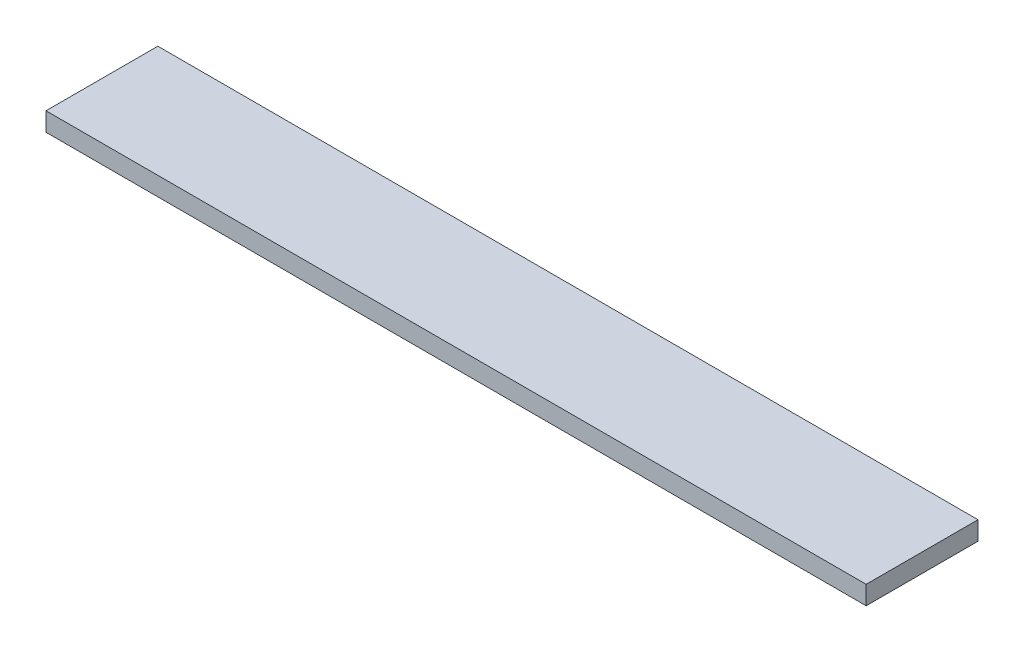
SolidWorks part; units mm, degrees
ref_plane "Front Plane" through (0, 0, 0) normal (0, 0, 1) x (1, 0, 0)
ref_plane "Top Plane" through (0, 0, 0) normal (0, 1, 0) x (1, 0, 0)
ref_plane "Right Plane" through (0, 0, 0) normal (1, 0, 0) x (0, 0, -1)
sketch "Sketch1" plane through (0, 0, 0) normal (0, 1, 0) x (1, 0, 0)
  line L1 (0, 0) -> (2200, 0)
  line L2 (0, 0) -> (0, 300)
  line L3 (0, 300) -> (2200, 300)
  line L4 (2200, 0) -> (2200, 300)
  dimension "D1" = 300
  dimension "D2" = 2200
extrude "Boss-Extrude1" add sketch "Sketch1" along normal blind 50
